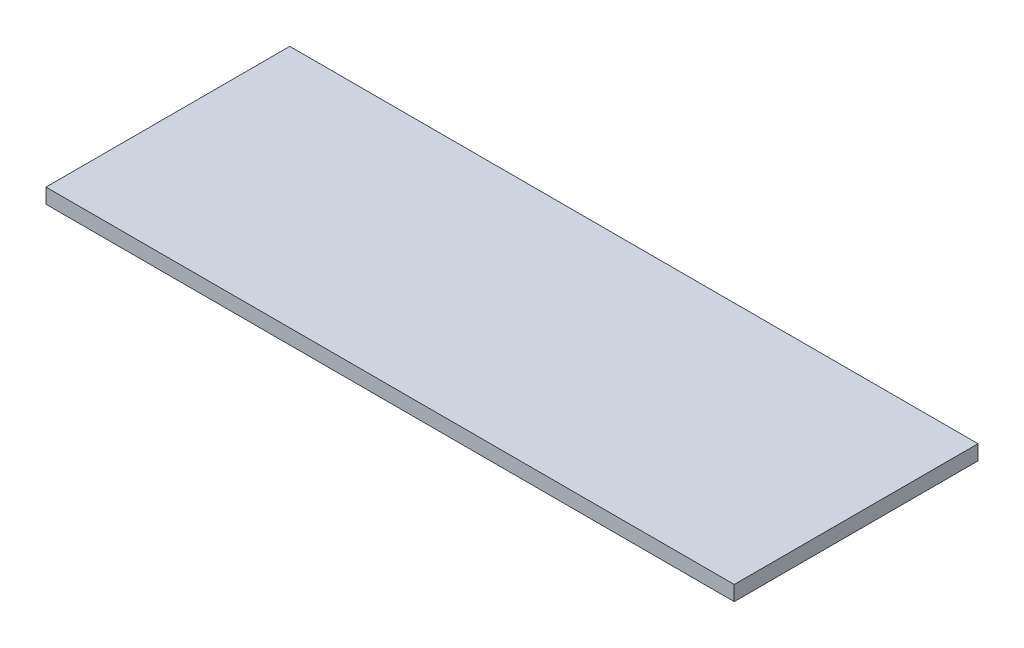
SolidWorks part; units mm, degrees
ref_plane "Front Plane" through (0, 0, 0) normal (0, 0, 1) x (1, 0, 0)
ref_plane "Top Plane" through (0, 0, 0) normal (0, 1, 0) x (1, 0, 0)
ref_plane "Right Plane" through (0, 0, 0) normal (1, 0, 0) x (0, 0, -1)
sketch "Sketch1" plane through (0, 0, 0) normal (0, 1, 0) x (1, 0, 0)
  line L1 (76.2, -26.9875) -> (-76.2, -26.9875)
  line L2 (76.2, -26.9875) -> (76.2, 26.9875)
  line L3 (76.2, 26.9875) -> (-76.2, 26.9875)
  line L4 (-76.2, -26.9875) -> (-76.2, 26.9875)
  line L5 (76.2, -26.9875) -> (-76.2, 26.9875) construction
  line L6 (76.2, 26.9875) -> (-76.2, -26.9875) construction
  point P0 (0, 0)
  dimension "D1" = 152.4
  dimension "D2" = 53.975
extrude "Boss-Extrude1" add sketch "Sketch1" along normal blind 3.302
equation "\"thick\"= 0.125in"
equation "\"D2@Sketch1\"=2+\"thick\""
